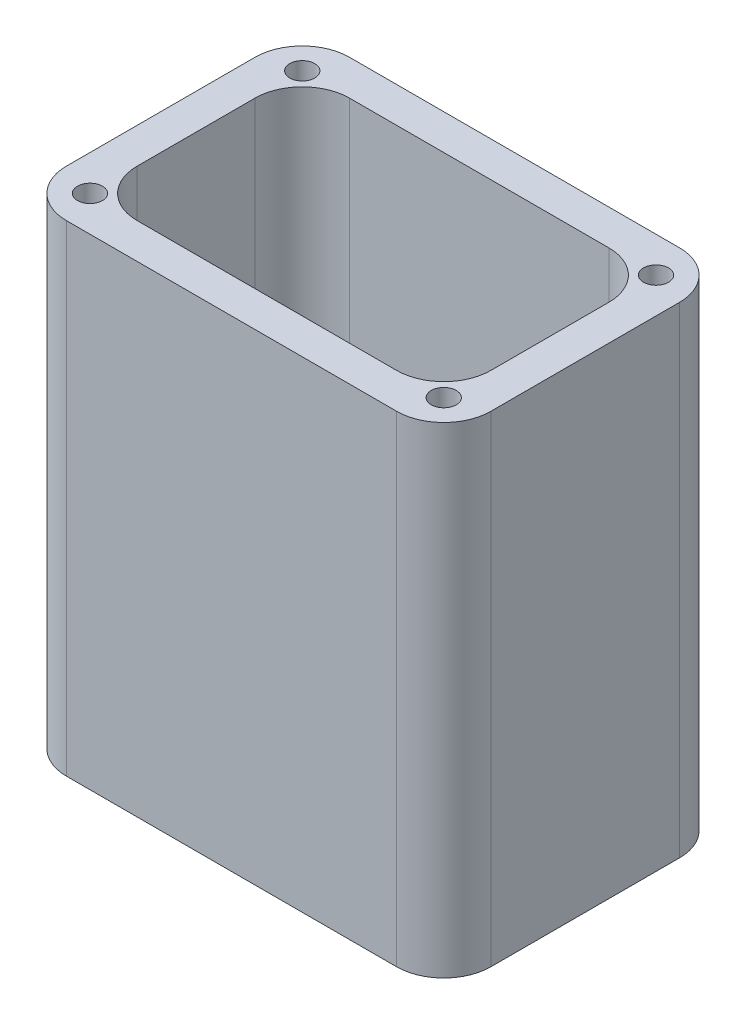
SolidWorks part; units mm, degrees
ref_plane "前视基准面" through (0, 0, 0) normal (0, 0, 1) x (1, 0, 0)
ref_plane "上视基准面" through (0, 0, 0) normal (0, 1, 0) x (1, 0, 0)
ref_plane "右视基准面" through (0, 0, 0) normal (1, 0, 0) x (0, 0, -1)
other "Configuration Table"
sketch "草图1" plane through (0, 0, 0) normal (0, 1, 0) x (1, 0, 0)
  line L0 (0, 30) -> (0, -30) construction
  line L1 (-35, 30) -> (35, 30)
  line L2 (-45, 20) -> (-45, -20)
  line L3 (-35, -30) -> (35, -30)
  line L4 (45, 20) -> (45, -20)
  line L5 (-45, 30) -> (45, -30) construction
  line L6 (-45, -30) -> (45, 30) construction
  line L7 (-45, 0) -> (45, 0) construction
  line L9 (-27.5, 22.5) -> (27.5, 22.5)
  line L10 (-37.5, 12.5) -> (-37.5, -12.5)
  line L11 (-27.5, -22.5) -> (27.5, -22.5)
  line L12 (37.5, 12.5) -> (37.5, -12.5)
  line L13 (-37.5, 22.5) -> (37.5, -22.5) construction
  line L14 (-37.5, -22.5) -> (37.5, 22.5) construction
  circle A0 centre (-37.5, 22.5) radius 2.65
  circle A1 centre (37.5, 22.5) radius 2.65
  circle A2 centre (37.5, -22.5) radius 2.65
  circle A3 centre (-37.5, -22.5) radius 2.65
  arc A4 (35, -30) -> (45, -20) centre (35, -20) ccw
  arc A5 (-45, -20) -> (-35, -30) centre (-35, -20) ccw
  arc A6 (35, 30) -> (45, 20) centre (35, 20) cw
  arc A7 (-35, 30) -> (-45, 20) centre (-35, 20) ccw
  arc A8 (27.5, 22.5) -> (37.5, 12.5) centre (27.5, 12.5) cw
  arc A9 (27.5, -22.5) -> (37.5, -12.5) centre (27.5, -12.5) ccw
  arc A10 (-37.5, -12.5) -> (-27.5, -22.5) centre (-27.5, -12.5) ccw
  arc A11 (-27.5, 22.5) -> (-37.5, 12.5) centre (-27.5, 12.5) ccw
  point P0 (0, 0)
  point P30 (0, 0)
  dimension "D5" = 5.3
  dimension "D6" = 10
  dimension "D7" = 10
  dimension "D1" = 90
  dimension "D2" = 60
  dimension "D3" = 75
  dimension "D4" = 45
extrude "凸台-拉伸1" add sketch "草图1" along normal blind 102
